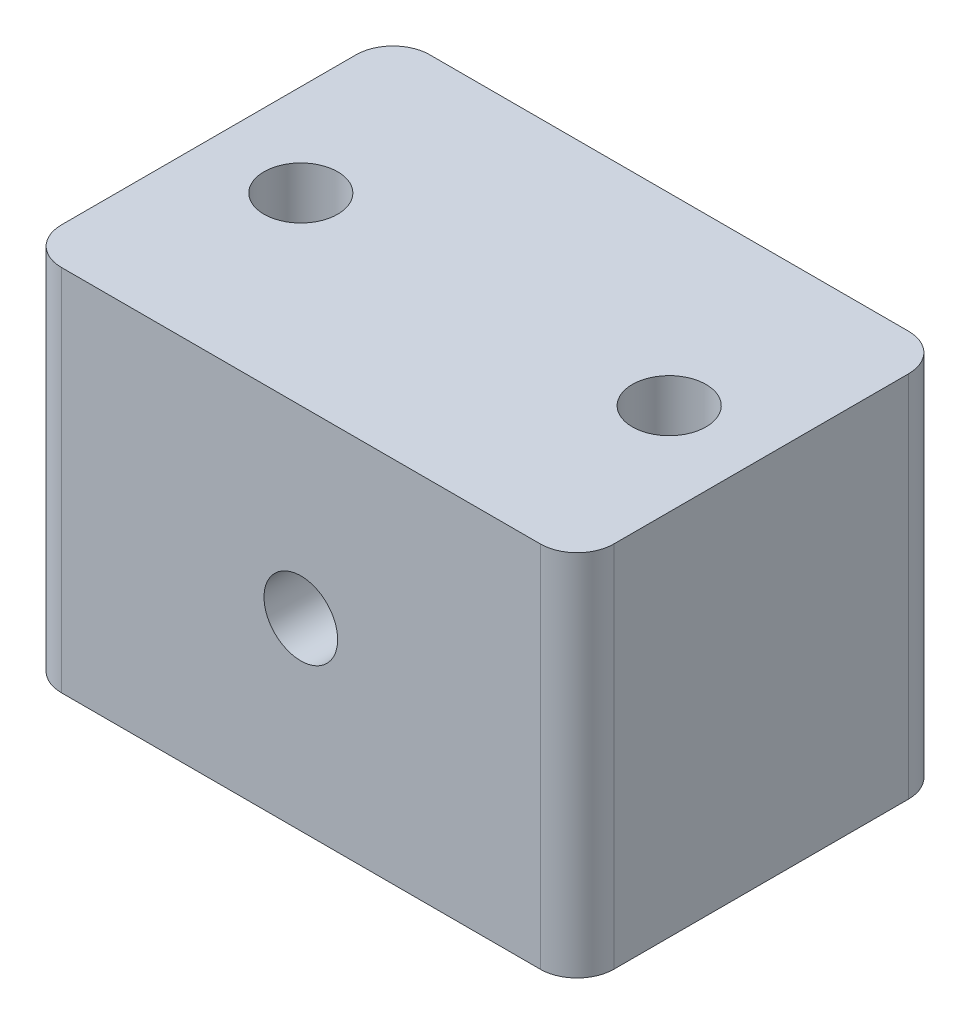
SolidWorks part; units mm, degrees
ref_plane "Alzado" through (0, 0, 0) normal (0, 0, 1) x (1, 0, 0)
ref_plane "Planta" through (0, 0, 0) normal (0, 1, 0) x (1, 0, 0)
ref_plane "Vista lateral" through (0, 0, 0) normal (1, 0, 0) x (0, 0, -1)
sketch "Croquis1" plane through (0, 0, 0) normal (0, 0, 1) x (1, 0, 0)
  line L0 (-18.2221, 5.2723) -> (-3.2221, 5.2723) construction
  line L1 (-18.2221, 10.2723) -> (-3.2221, 10.2723)
  line L2 (-18.2221, 10.2723) -> (-18.2221, 0.2723)
  line L3 (-18.2221, 0.2723) -> (-3.2221, 0.2723)
  line L4 (-3.2221, 10.2723) -> (-3.2221, 0.2723)
  circle A0 centre (-10.7221, 5.2723) radius 1
  dimension "D3" = 2
  dimension "D1" = 15
  dimension "D2" = 10
extrude "Saliente-Extruir1" add sketch "Croquis1" along normal blind 10
sketch "Croquis2" plane through (0, 10.2723, 0) normal (0, 1, 0) x (-1, 0, 0)
  line L0 (18.2221, 5) -> (3.2221, 5) construction
  line L1 (18.2221, 10) -> (18.2221, 0) construction
  line L2 (3.2221, 10) -> (3.2221, 0) construction
  circle A0 centre (15.7221, 5) radius 1
  circle A1 centre (5.7221, 5) radius 1
  dimension "D1" = 2
  dimension "D2" = 2
  dimension "D3" = 10
  dimension "D4" = 2.5
extrude "Cortar-Extruir1" cut sketch "Croquis2" against normal blind 10
fillet "Redondeo1" radius 1 4 edges at (-18.2221, 5.2723, 0) (-18.2221, 5.2723, 10) (-3.2221, 5.2723, 0) (-3.2221, 5.2723, 10)
